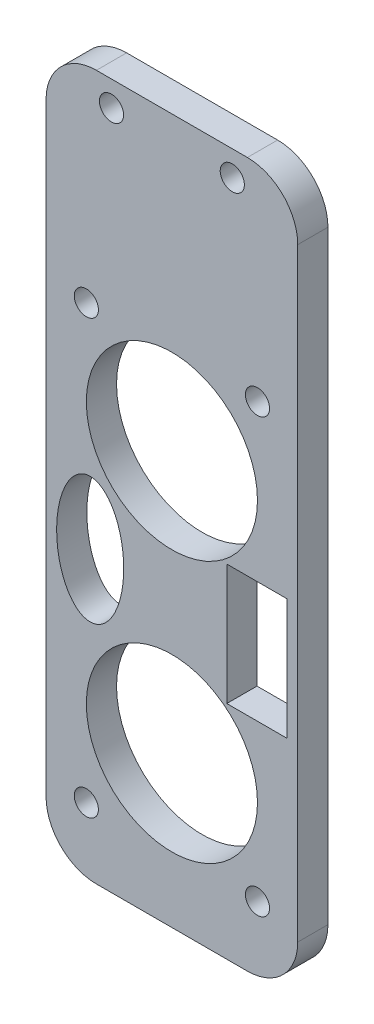
SolidWorks part; units mm, degrees
ref_plane "Front Plane" through (0, 0, 0) normal (0, 0, 1) x (1, 0, 0)
ref_plane "Top Plane" through (0, 0, 0) normal (0, 1, 0) x (1, 0, 0)
ref_plane "Right Plane" through (0, 0, 0) normal (1, 0, 0) x (0, 0, -1)
sketch "Sketch1" plane through (0, 0, 0) normal (0, 0, 1) x (1, 0, 0)
  line L1 (0, 0) -> (25, 0)
  line L2 (0, 0) -> (0, -70)
  line L3 (0, -70) -> (25, -70)
  line L4 (25, 0) -> (25, -70)
  circle A0 centre (12.5, -29) radius 8.5
  circle A1 centre (12.5, -55) radius 8.5
  circle A2 centre (21, -63.5) radius 1.2
  circle A3 centre (4, -63.5) radius 1.2
  circle A4 centre (4, -20.5) radius 1.2
  circle A5 centre (21, -20.5) radius 1.2
  dimension "D3" = 12.5
  dimension "D6" = 8.5
  dimension "D1" = 70
  dimension "D2" = 25
  dimension "D4" = 26
  dimension "D5" = 15
  dimension "D7" = 8.5
  dimension "D8" = 2
  dimension "D9" = 2
extrude "Boss-Extrude1" add sketch "Sketch1" along normal blind 3
fillet "Fillet1" radius 5 4 edges at (25, -70, 1.5) (0, -70, 1.5) (0, 0, 1.5) (25, 0, 1.5)
hole_wizard "M2 Clearance Hole1" positions "Sketch2" profile "Sketch3" hole size "M2" standard "ANSI Metric"
sketch "Sketch2" plane through (0, 0, 3) normal (0, 0, 1) x (1, 0, 0)
  line L0 (20, 0) -> (5, 0) construction
  line L1 (0, -5) -> (0, -65) construction
  point P0 (6.5, -2.5)
  point P2 (18.5, -2.5)
  dimension "D1" = 2.5
  dimension "D2" = 12
  dimension "D3" = 6.5
sketch "Sketch3" plane through (6.5, -2.5, 3) normal (1, 0, 0) x (0, -1, 0)
  line L0 (0, 0) -> (0, 3.72)
  line L1 (0, 3.72) -> (1.2, 2.999)
  line L2 (1.2, 2.999) -> (1.2, 0)
  line L5 (1.2, 0) -> (0, 0)
  line L10 (0, 3.72) -> (-1.2, 2.999) construction
  line L11 (0, -6.35) -> (0, 107.95) construction
  dimension "Hole Dia." = 2.4
  dimension "Hole Depth" = 2.999
  dimension "Drill Angle" = 118
sketch "Sketch4" plane through (0, 0, 3) normal (0, 0, 1) x (1, 0, 0)
  line L0 (5, -70) -> (20, -70) construction
  line L1 (17.9538, -36) -> (23.9538, -36)
  line L2 (17.9538, -36) -> (17.9538, -48)
  line L3 (17.9538, -48) -> (23.9538, -48)
  line L4 (23.9538, -36) -> (23.9538, -48)
  dimension "D1" = 12
  dimension "D2" = 6
  dimension "D3" = 22
extrude "Cut-Extrude1" cut sketch "Sketch4" against normal blind 3
sketch "Sketch8" plane through (0, 0, 0) normal (0, 0, -1) x (-1, 0, 0)
  circle A0 centre (-12.5, -29) radius 8.5 construction
  ellipse E0 centre (-4.382, -41.5) end of major axis (-4.382, -47.7649) minor radius 3.3316
  dimension "D1" = 12.5
extrude "Cut-Extrude2" cut sketch "Sketch8" against normal blind 3
